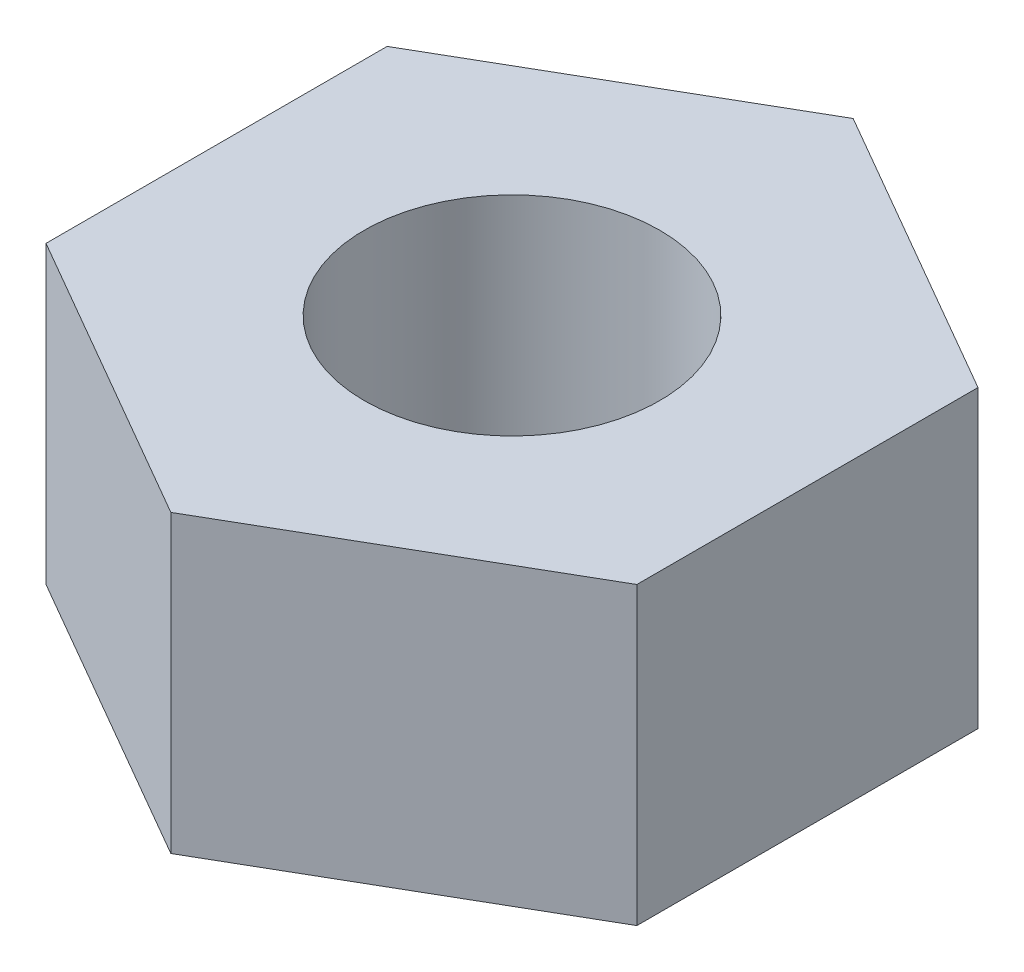
SolidWorks part; units mm, degrees
ref_plane "Front Plane" through (0, 0, 0) normal (0, 0, 1) x (1, 0, 0)
ref_plane "Top Plane" through (0, 0, 0) normal (0, 1, 0) x (1, 0, 0)
ref_plane "Right Plane" through (0, 0, 0) normal (1, 0, 0) x (0, 0, -1)
sketch "Sketch1" plane through (0, 0, 0) normal (0, 1, 0) x (1, 0, 0)
  line L0 (0, 0) -> (0, 3.4641) construction
  line L1 (0, 3.4641) -> (-3, 1.7321)
  line L2 (-3, 1.7321) -> (-3, -1.7321)
  line L3 (-3, -1.7321) -> (0, -3.4641)
  line L4 (0, -3.4641) -> (3, -1.7321)
  line L5 (3, -1.7321) -> (3, 1.7321)
  line L6 (3, 1.7321) -> (0, 3.4641)
  circle A0 centre (0, 0) radius 3 construction
  circle A1 centre (0, 0) radius 1.5
  dimension "D3" = 3
  dimension "D1" = 6
  dimension "D2" = 0
extrude "Boss-Extrude1" add sketch "Sketch1" along normal blind 3
